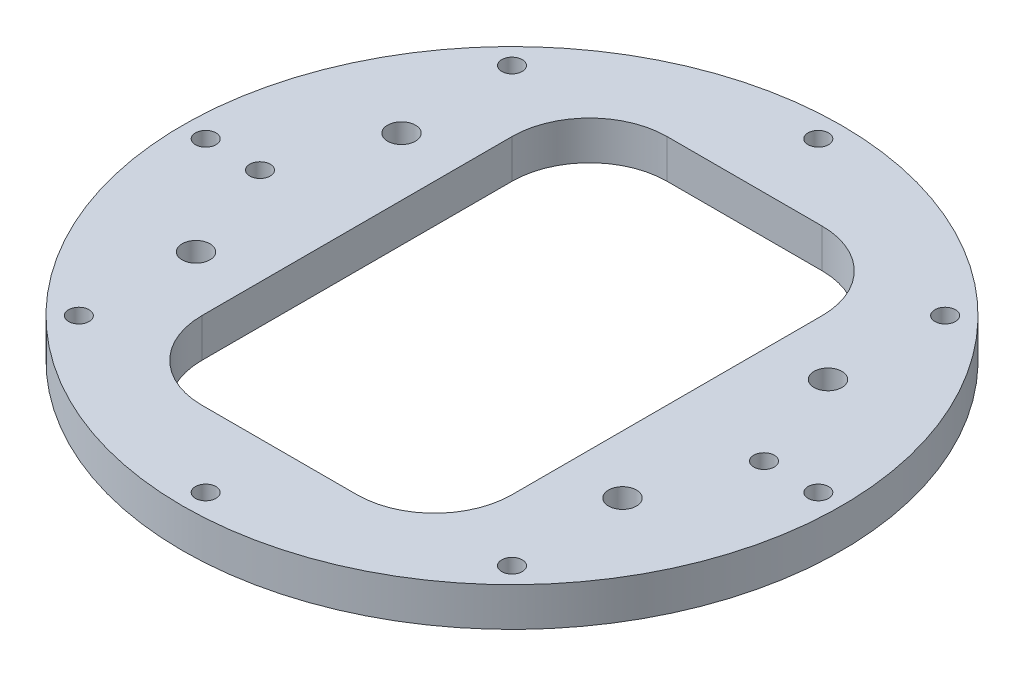
SolidWorks part; units mm, degrees
ref_plane "前视基准面" through (0, 0, 0) normal (0, 0, 1) x (1, 0, 0)
ref_plane "上视基准面" through (0, 0, 0) normal (0, 1, 0) x (1, 0, 0)
ref_plane "右视基准面" through (0, 0, 0) normal (1, 0, 0) x (0, 0, -1)
other "Configuration Table"
sketch "草图1" plane through (0, 0, 0) normal (0, 1, 0) x (1, 0, 0)
  line L0 (-1000, 0) -> (49000, 0) construction
  line L1 (-25, -50) -> (25, -50)
  line L2 (-25, -50) -> (-25, 50)
  line L3 (-25, 50) -> (25, 50)
  line L4 (25, -50) -> (25, 50)
  line L5 (-25, -50) -> (25, 50) construction
  line L6 (-25, 50) -> (25, -50) construction
  line L7 (0, -1000) -> (0, 49000) construction
  line L8 (0, 85.5) -> (0, 72.5)
  line L10 (-40, -50) -> (40, -50)
  line L11 (-40, -50) -> (-40, 50)
  line L12 (-40, 50) -> (40, 50)
  line L13 (40, -50) -> (40, 50)
  line L14 (-40, -50) -> (40, 50) construction
  line L15 (-40, 50) -> (40, -50) construction
  circle A0 centre (0, 0) radius 72.5
  circle A1 centre (0, 0) radius 85.5
  circle A2 centre (0, 79) radius 2.65
  circle A3 centre (55.8614, 55.8614) radius 2.65
  circle A4 centre (79, 0) radius 2.65
  circle A5 centre (55.8614, -55.8614) radius 2.65
  circle A6 centre (0, -79) radius 2.65
  circle A7 centre (-55.8614, -55.8614) radius 2.65
  circle A8 centre (-79, 0) radius 2.65
  circle A9 centre (-55.8614, 55.8614) radius 2.65
  point P33 (0, 0)
  dimension "D1" = 145
  dimension "D5" = 5.3
  dimension "D2" = 50
  dimension "D3" = 100
  dimension "D7" = 80
  dimension "D8" = 100
  dimension "D4" = 13
  dimension "D6" = 8
extrude "凸台-拉伸3" add sketch "草图1" along normal blind 10
sketch "草图10" plane through (0, 10, 0) normal (0, 1, 0) x (1, 0, 0)
  line L0 (0, 0) -> (55, 0)
  line L1 (40, -50) -> (40, 50) construction
  line L2 (55, 0) -> (55, 26.5)
  line L3 (0, -1000) -> (0, 49000) construction
  line L4 (55, 0) -> (65, 0)
  circle A0 centre (55, 26.5) radius 3.6
  circle A1 centre (55, -26.5) radius 3.6
  circle A2 centre (-55, -26.5) radius 3.6
  circle A3 centre (-55, 26.5) radius 3.6
  circle A4 centre (0, 0) radius 72.5
  circle A5 centre (65, 0) radius 2.65
  circle A6 centre (-65, 0) radius 2.65
  dimension "D3" = 7.2
  dimension "D4" = 145
  dimension "D6" = 5.3
  dimension "D1" = 15
  dimension "D2" = 26.5
  dimension "D5" = 10
extrude "切除-拉伸2" cut sketch "草图10" against normal blind 10
sketch "草图11" plane through (0, 10, 0) normal (0, 1, 0) x (1, 0, 0)
  line L1 (-40, -60) -> (40, -60)
  line L2 (-40, -60) -> (-40, 60)
  line L3 (-40, 60) -> (40, 60)
  line L4 (40, -60) -> (40, 60)
  line L5 (-40, -60) -> (40, 60) construction
  line L6 (-40, 60) -> (40, -60) construction
  dimension "D2" = 120
  dimension "D3" = 80
extrude "切除-拉伸3" cut sketch "草图11" against normal blind 10
fillet "圆角1" radius 20 4 edges at (40, 5, 60) (-40, 5, 60) (40, 5, -60) (-40, 5, -60)
sketch "草图12" plane through (0, 10, 0) normal (0, 1, 0) x (1, 0, 0)
  circle A0 centre (0, 0) radius 85
  circle A1 centre (0, 0) radius 85.5
  dimension "D1" = 170
extrude "切除-拉伸4" cut sketch "草图12" against normal blind 10
